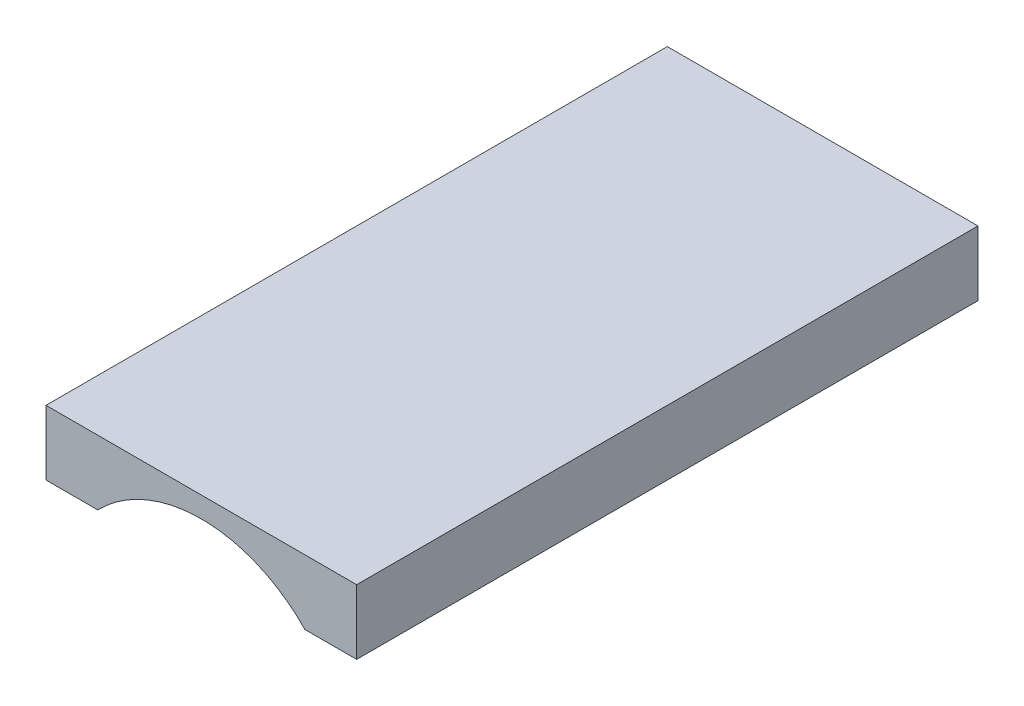
SolidWorks part; units mm, degrees
ref_plane "Front Plane" through (0, 0, 0) normal (0, 0, 1) x (1, 0, 0)
ref_plane "Top Plane" through (0, 0, 0) normal (0, 1, 0) x (1, 0, 0)
ref_plane "Right Plane" through (0, 0, 0) normal (1, 0, 0) x (0, 0, -1)
sketch "Sketch1" plane through (0, 0, 0) normal (1, 0, 0) x (0, 0, -1)
  line L0 (0, 0) -> (0, 6.25)
  line L1 (0, 6.25) -> (60, 6.25)
  line L2 (60, 6.25) -> (60, 0)
  line L3 (60, 0) -> (0, 0)
  dimension "D1" = 60
  dimension "D2" = 6.25
extrude "Boss-Extrude1" add sketch "Sketch1" along normal blind 30
sketch "Sketch2" plane through (0, 0, 0) normal (0, 0, 1) x (1, 0, 0)
  line L0 (30, 0) -> (0, 0) construction
  line L1 (5, 0) -> (25, 0)
  arc A0 (5, 0) -> (25, 0) centre (15, -9.6397) cw
  point P3 (15, 4.25)
  dimension "D1" = 4.25
  dimension "D2" = 5
  dimension "D3" = 5
extrude "Cut-Extrude1" cut sketch "Sketch2" against normal blind 45 and the other way through all
sketch "Sketch3" plane through (0, 0, -60) normal (0, 0, -1) x (-1, 0, 0)
  line L5 (-30, 0) -> (0, 0) construction
  line L7 (-30, 6.25) -> (0, 6.25) construction
  line L12 (-10, 2) -> (-10, 5)
  line L13 (-10, 5) -> (-20, 5)
  line L15 (-20, 2) -> (-10, 2)
  line L16 (-20, 2) -> (-18.5, 3.5)
  line L17 (-18.5, 3.5) -> (-20, 5)
  point P7 (0, 0)
  point P8 (-15, 5)
  point P9 (-10, 3.5)
  point P12 (-15, 6.25)
  point P13 (0, 0)
  point P14 (0, 0)
  dimension "D1" = 10
  dimension "D2" = 2
  dimension "D3" = 3
extrude "Cut-Extrude2" cut sketch "Sketch3" against normal blind 13
